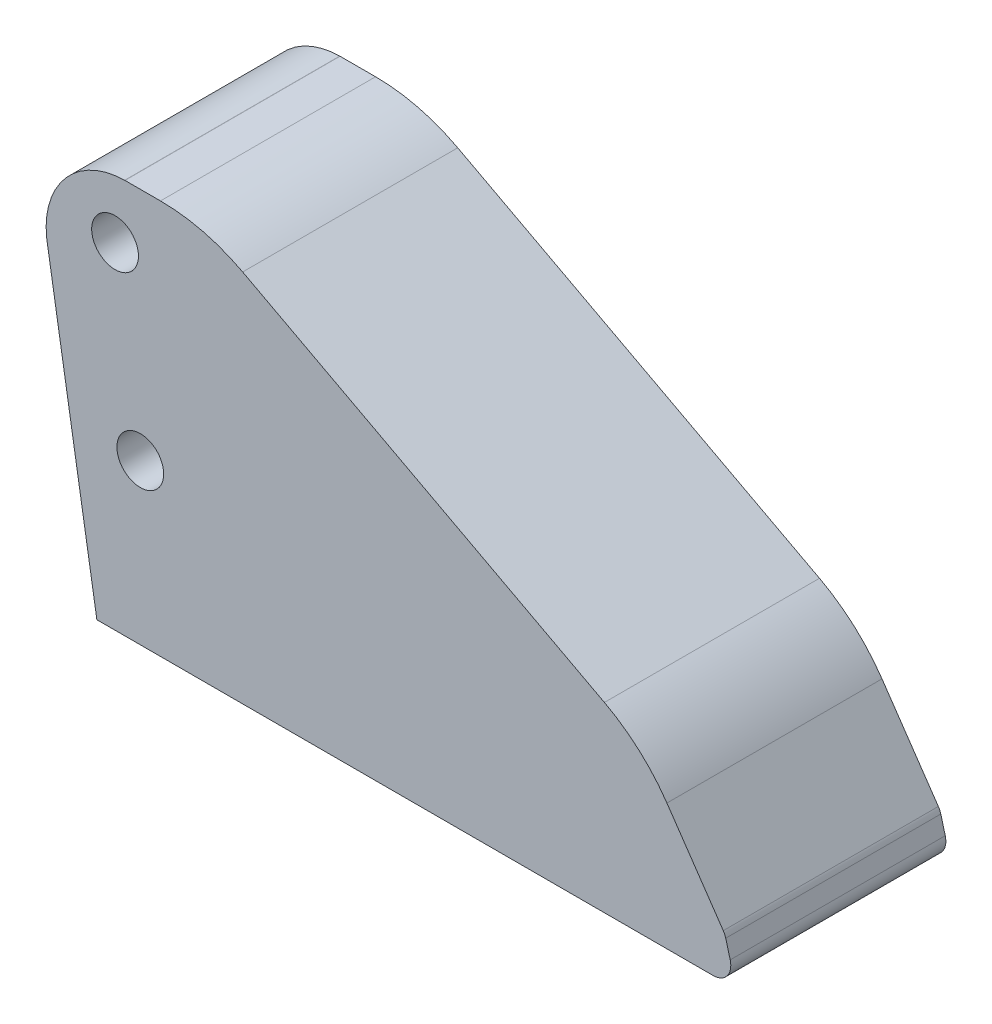
SolidWorks part; units mm, degrees
ref_plane "Front Plane" through (0, 0, 0) normal (0, 0, 1) x (1, 0, 0)
ref_plane "Top Plane" through (0, 0, 0) normal (0, 1, 0) x (1, 0, 0)
ref_plane "Right Plane" through (0, 0, 0) normal (1, 0, 0) x (0, 0, -1)
sketch "Sketch1" plane through (0, 0, 0) normal (0, 0, 1) x (1, 0, 0)
  line L0 (0, 0) -> (42.98, -6.863)
  line L1 (-2.4872, 2.4759) -> (-7.7391, 34.4271)
  line L2 (5.6424, 49.761) -> (11.7224, 49.761)
  line L3 (25.782, 46.2625) -> (87.6805, 13.4239)
  line L4 (98.3784, 3.8655) -> (108.019, -10.2215)
  line L6 (106.3066, -17.7446) -> (98.2366, -17.7446)
  line L7 (109.203, -13.963) -> (108.4396, -11.1342)
  line L8 (106.3066, -17.7446) -> (106.3066, -17.138)
  line L9 (106.3066, -17.138) -> (96.8886, -17.138)
  line L10 (96.8886, -17.138) -> (96.8886, -17.6533)
  line L12 (96.8886, -17.138) -> (97.3722, -17.138)
  line L13 (96.8886, -17.138) -> (96.8886, -17.6533)
  line L15 (97.3722, -17.138) -> (97.3722, -17.7072)
  line L16 (97.6535, -17.138) -> (98.1601, -17.138)
  line L17 (97.6535, -17.138) -> (97.6535, -17.7276)
  line L19 (98.1601, -17.138) -> (98.1601, -17.7443)
  line L20 (98.3784, -17.138) -> (98.822, -17.138)
  line L21 (98.3784, -17.138) -> (98.3784, -17.7446)
  line L22 (98.3784, -17.7446) -> (98.822, -17.7446)
  line L23 (98.822, -17.138) -> (98.822, -17.7446)
  line L24 (99.0508, -17.138) -> (99.4921, -17.138)
  line L25 (99.0508, -17.138) -> (99.0508, -17.7446)
  line L26 (99.0508, -17.7446) -> (99.4921, -17.7446)
  line L27 (99.4921, -17.138) -> (99.4921, -17.7446)
  line L28 (99.77, -17.138) -> (100.3093, -17.138)
  line L29 (99.77, -17.138) -> (99.77, -17.7446)
  line L30 (99.77, -17.7446) -> (100.3093, -17.7446)
  line L31 (100.3093, -17.138) -> (100.3093, -17.7446)
  line L32 (100.5218, -17.138) -> (101.0693, -17.138)
  line L33 (100.5218, -17.138) -> (100.5218, -17.7446)
  line L34 (100.5218, -17.7446) -> (101.0693, -17.7446)
  line L35 (101.0693, -17.138) -> (101.0693, -17.7446)
  line L36 (101.1918, -17.138) -> (101.8783, -17.138)
  line L37 (101.1918, -17.138) -> (101.1918, -17.7446)
  line L38 (101.1918, -17.7446) -> (101.8783, -17.7446)
  line L39 (101.8783, -17.138) -> (101.8783, -17.7446)
  line L40 (102.0499, -17.138) -> (102.5974, -17.138)
  line L41 (102.0499, -17.138) -> (102.0499, -17.7446)
  line L42 (102.0499, -17.7446) -> (102.5974, -17.7446)
  line L43 (102.5974, -17.138) -> (102.5974, -17.7446)
  line L44 (102.7132, -17.138) -> (103.3211, -17.138)
  line L45 (102.7132, -17.138) -> (102.7132, -17.7446)
  line L46 (102.7132, -17.7446) -> (103.3211, -17.7446)
  line L47 (103.3211, -17.138) -> (103.3211, -17.7446)
  line L48 (103.5047, -17.138) -> (103.9775, -17.138)
  line L49 (103.5047, -17.138) -> (103.5047, -17.7446)
  line L50 (103.5047, -17.7446) -> (103.9775, -17.7446)
  line L51 (103.9775, -17.138) -> (103.9775, -17.7446)
  line L52 (104.1802, -17.138) -> (104.682, -17.138)
  line L53 (104.1802, -17.138) -> (104.1802, -17.7446)
  line L54 (104.1802, -17.7446) -> (104.682, -17.7446)
  line L55 (104.682, -17.138) -> (104.682, -17.7446)
  line L56 (104.8557, -17.138) -> (105.4154, -17.138)
  line L57 (104.8557, -17.138) -> (104.8557, -17.7446)
  line L58 (104.8557, -17.7446) -> (105.4154, -17.7446)
  line L59 (105.4154, -17.138) -> (105.4154, -17.7446)
  line L60 (105.5432, -17.138) -> (105.8786, -17.138)
  line L61 (105.5432, -17.138) -> (105.5432, -17.7446)
  line L62 (105.5432, -17.7446) -> (105.8786, -17.7446)
  line L63 (105.8786, -17.138) -> (105.8786, -17.7446)
  line L64 (105.9847, -17.138) -> (106.3066, -17.138)
  line L65 (105.9847, -17.138) -> (105.9847, -17.7446)
  line L66 (105.9847, -17.7446) -> (106.3066, -17.7446)
  line L67 (106.3066, -17.138) -> (106.3066, -17.7446)
  arc A0 (0, 0) -> (-2.4872, 2.4759) centre (0.473, 2.9625) cw
  arc A1 (-7.7391, 34.4271) -> (-7.7605, 34.5823) centre (-4.7789, 34.9137) cw
  arc A4 (5.5908, 49.7606) -> (5.6424, 49.761) centre (5.6424, 46.761) cw
  arc A5 (11.7224, 49.761) -> (25.782, 46.2625) centre (11.7224, 19.761) cw
  arc A6 (87.6805, 13.4239) -> (98.3784, 3.8655) centre (73.6209, -13.0776) cw
  arc A7 (108.019, -10.2215) -> (108.4396, -11.1342) centre (105.5432, -11.9158) cw
  arc A8 (109.203, -13.963) -> (106.3066, -17.7446) centre (106.3066, -14.7446) cw
  arc A9 (98.2366, -17.7446) -> (91.4468, -15.0862) centre (98.2366, -7.7446) cw
  arc A10 (91.4468, -15.0862) -> (47.9937, -6.379) centre (62.5971, -46.2806) ccw
  arc A14 (42.98, -6.863) -> (47.9937, -6.379) centre (44.5568, 3.0119) ccw
  arc A15 (-7.7605, 34.5823) -> (-2.9945, 46.5363) centre (5.8258, 36.0926) cw
  arc A16 (-2.9945, 46.5363) -> (5.5908, 49.7606) centre (5.8258, 36.0926) cw
  circle A17 centre (3.9484, 39.6959) radius 4
  circle A18 centre (8.2675, 9.5617) radius 4
  dimension "D2" = 3
  dimension "D4" = 3
  dimension "D5" = 13.67
  dimension "D6" = 13.67
  dimension "D7" = 3
  dimension "D9" = 30
  dimension "D11" = 30
  dimension "D13" = 3
  dimension "D15" = 3
  dimension "D17" = 10
  dimension "D18" = 42.49
  dimension "D19" = 10
  dimension "D23" = 8
  dimension "D24" = 8
  dimension "D1" = 42.98
  dimension "D3" = 32.38
  dimension "D8" = 6.08
  dimension "D10" = 70.07
  dimension "D12" = 17.07
  dimension "D14" = 2.93
  dimension "D16" = 8.07
  dimension "D20" = 37.22
  dimension "D22" = 47.2851
extrude "Boss-Extrude1" add sketch "Sketch1" along normal blind 36.8 contours A16 A15 A1 L1 A0 L0 A14 A10 A9 L10 L9 L8 A8 L7 A7 L4 A6 L3 A5 L2 A4 A18 A17 | A9 L15 L9 L10 | A9 L19 L9 L17 | L23 L9 L21 L6 | L27 L9 L25 L6 | L31 L9 L29 L6 | L35 L9 L33 L6 | L39 L9 L37 L6 | L43 L9 L41 L6 | L47 L9 L45 L6 | L51 L9 L49 L6 | L55 L9 L53 L6 | L59 L9 L57 L6 | L9 L65 L6 L8 | L63 L62 L61 L60
ref_plane "Plane1" through (0, -40, 0) normal (0, 1, 0) x (1, 0, 0)
sketch "Sketch2" plane through (0, -40, 0) normal (0, 1, 0) x (1, 0, 0)
  line L0 (47.9937, -36.8) -> (91.4468, -36.8) construction
  line L1 (47.9937, -36.8) -> (91.4468, -36.8)
  line L2 (91.4468, -36.8) -> (91.4468, 0) construction
  line L3 (91.4468, 0) -> (47.9937, 0) construction
  line L4 (47.9937, -36.8) -> (47.9937, 0) construction
  line L5 (91.4468, -36.8) -> (91.4468, 0)
  line L6 (91.4468, 0) -> (47.9937, 0)
  line L7 (47.9937, -36.8) -> (47.9937, 0)
  line L8 (52.9937, -31.8) -> (86.4468, -31.8)
  line L9 (86.4468, -31.8) -> (86.4468, -5)
  line L10 (86.4468, -5) -> (52.9937, -5)
  line L11 (52.9937, -31.8) -> (52.9937, -5)
  dimension "D1" = 5
extrude "Cut-Extrude1" cut sketch "Sketch2" along normal blind 45 contours L11 L8 L9 L10
scale "Scale1" bodies to scale 102 scale about centroid uniform scaling yes scale factor 0.7
sketch "Sketch3" plane through (0, 0, 31.28) normal (0, 0, 1) x (1, 0, 0)
  line L0 (10.217, 6.6179) -> (12.5435, -7.5364)
  line L1 (12.5435, -7.5364) -> (86.3726, -7.5364)
  line L2 (86.3726, -7.5364) -> (86.1473, -7.5364) construction
  line L3 (86.3726, -7.5364) -> (86.3726, -6.9502)
  line L4 (86.3726, -6.9502) -> (60.8118, 6.6179)
  line L5 (60.8118, 6.6179) -> (10.217, 6.6179)
  arc A0 (86.3726, -7.5364) -> (88.4001, -4.8893) centre (86.3726, -5.4364) ccw construction
  dimension "D1" = 14.1543
  dimension "D2" = 73.8291
extrude "Boss-Extrude2" add sketch "Sketch3" against normal up to surface (25.76 mm away) up to face at (74.1159, -2.169, 5.52)
